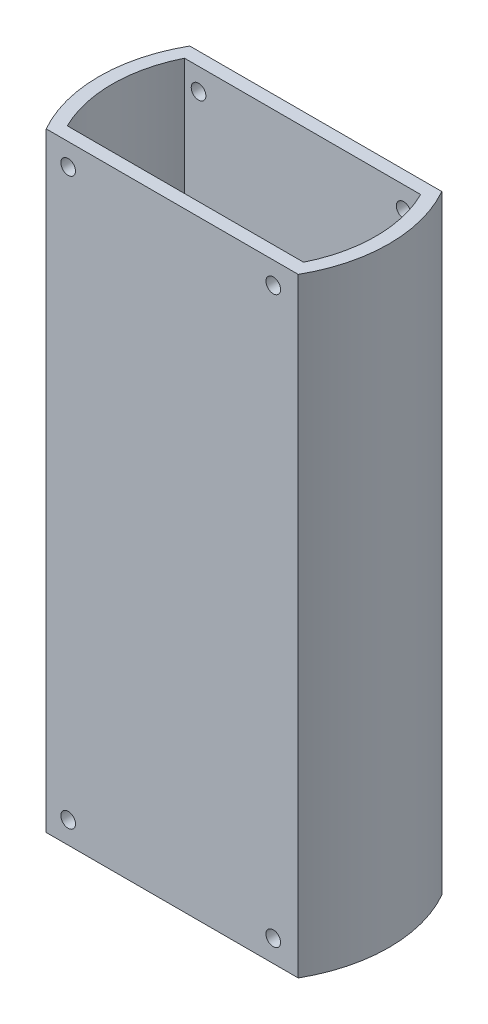
SolidWorks part; units mm, degrees
ref_plane "Front Plane" through (0, 0, 0) normal (0, 0, 1) x (1, 0, 0)
ref_plane "Top Plane" through (0, 0, 0) normal (0, 1, 0) x (1, 0, 0)
ref_plane "Right Plane" through (0, 0, 0) normal (1, 0, 0) x (0, 0, -1)
sketch "Sketch2" plane through (0, 0, 0) normal (0, 1, 0) x (1, 0, 0)
  line L0 (0, -20) -> (0, 20)
  line L1 (-45.2797, 20) -> (45.2797, 20)
  line L2 (-45.2797, -20) -> (45.2797, -20)
  line L3 (-43.0116, -24.5) -> (43.0116, -24.5)
  line L4 (-43.0116, 24.5) -> (43.0116, 24.5)
  circle A0 centre (0, 0) radius 49.5
  circle A1 centre (0, 0) radius 45
  point P7 (0, 0)
  point P9 (0, 20)
  point P13 (0, -20)
  point P16 (0, -24.5)
  point P19 (0, 24.5)
  dimension "D1" = 99
  dimension "D2" = 90
  dimension "D3" = 40
  dimension "D4" = 4.5
  dimension "D5" = 4.5
extrude "Boss-Extrude1" add sketch "Sketch2" along normal blind 208 contours A1 L1 A0 L2 | A1 L2 A0 L3 | L3 A1 L2 | A1 L3 A0 L2 | A1 L1 A0 L4 | A1 L2 A0 L1 | L1 A1 L4 | A1 L4 A0 L1
sketch "Sketch3" plane through (0, 0, 24.5) normal (0, 0, 1) x (1, 0, 0)
  line L0 (0, 208) -> (0, 0) construction
  line L1 (-43.0116, 208) -> (-35.5116, 208)
  line L2 (-43.0116, 208) -> (-43.0116, 200.5)
  line L3 (-43.0116, 200.5) -> (-35.5116, 200.5)
  line L4 (-35.5116, 208) -> (-35.5116, 200.5)
  line L5 (-43.0116, 208) -> (43.0116, 208) construction
  line L6 (-43.0116, 104) -> (43.0116, 104) construction
  line L7 (-43.0116, 208) -> (-43.0116, 0) construction
  line L8 (43.0116, 208) -> (43.0116, 0) construction
  line L9 (37.4884, 198.7679) -> (37.4884, 202.2321)
  line L10 (-32.5116, 198.7679) -> (-32.5116, 202.2321)
  line L11 (-32.5116, 202.2321) -> (-35.5116, 203.9641)
  line L12 (-35.5116, 203.9641) -> (-38.5116, 202.2321)
  line L13 (-38.5116, 202.2321) -> (-38.5116, 198.7679)
  line L14 (-38.5116, 198.7679) -> (-35.5116, 197.0359)
  line L15 (-35.5116, 197.0359) -> (-32.5116, 198.7679)
  line L16 (37.4884, 202.2321) -> (34.4884, 203.9641)
  line L17 (34.4884, 203.9641) -> (31.4884, 202.2321)
  line L18 (31.4884, 202.2321) -> (31.4884, 198.7679)
  line L19 (31.4884, 198.7679) -> (34.4884, 197.0359)
  line L20 (34.4884, 197.0359) -> (37.4884, 198.7679)
  line L21 (37.4884, 5.7679) -> (37.4884, 9.2321)
  line L22 (37.4884, 9.2321) -> (34.4884, 10.9641)
  line L23 (34.4884, 10.9641) -> (31.4884, 9.2321)
  line L24 (31.4884, 9.2321) -> (31.4884, 5.7679)
  line L25 (31.4884, 5.7679) -> (34.4884, 4.0359)
  line L26 (34.4884, 4.0359) -> (37.4884, 5.7679)
  line L27 (-32.5116, 5.7679) -> (-32.5116, 9.2321)
  line L28 (-32.5116, 9.2321) -> (-35.5116, 10.9641)
  line L29 (-35.5116, 10.9641) -> (-38.5116, 9.2321)
  line L30 (-38.5116, 9.2321) -> (-38.5116, 5.7679)
  line L31 (-38.5116, 5.7679) -> (-35.5116, 4.0359)
  line L32 (-35.5116, 4.0359) -> (-32.5116, 5.7679)
  line L33 (-43.0116, 0) -> (43.0116, 0) construction
  circle A0 centre (-35.5116, 200.5) radius 2.5
  circle A1 centre (34.4884, 200.5) radius 2.5
  circle A2 centre (34.4884, 7.5) radius 2.5
  circle A3 centre (-35.5116, 7.5) radius 2.5
  circle A4 centre (-35.5116, 200.5) radius 3 construction
  point P32 (-32.5116, 7.5)
  dimension "D3" = 5
  dimension "D1" = 7.5
  dimension "D2" = 7.5
  dimension "D8" = 4.5
  dimension "D9" = 7.5
  dimension "D10" = 7.5
  dimension "D6" = 2
  dimension "D4" = 2
  dimension "D5" = 2
  dimension "D7" = 2
extrude "Cut-Extrude1" cut sketch "Sketch3" against normal blind 60 contours A0 | A1 | A3 | A2
